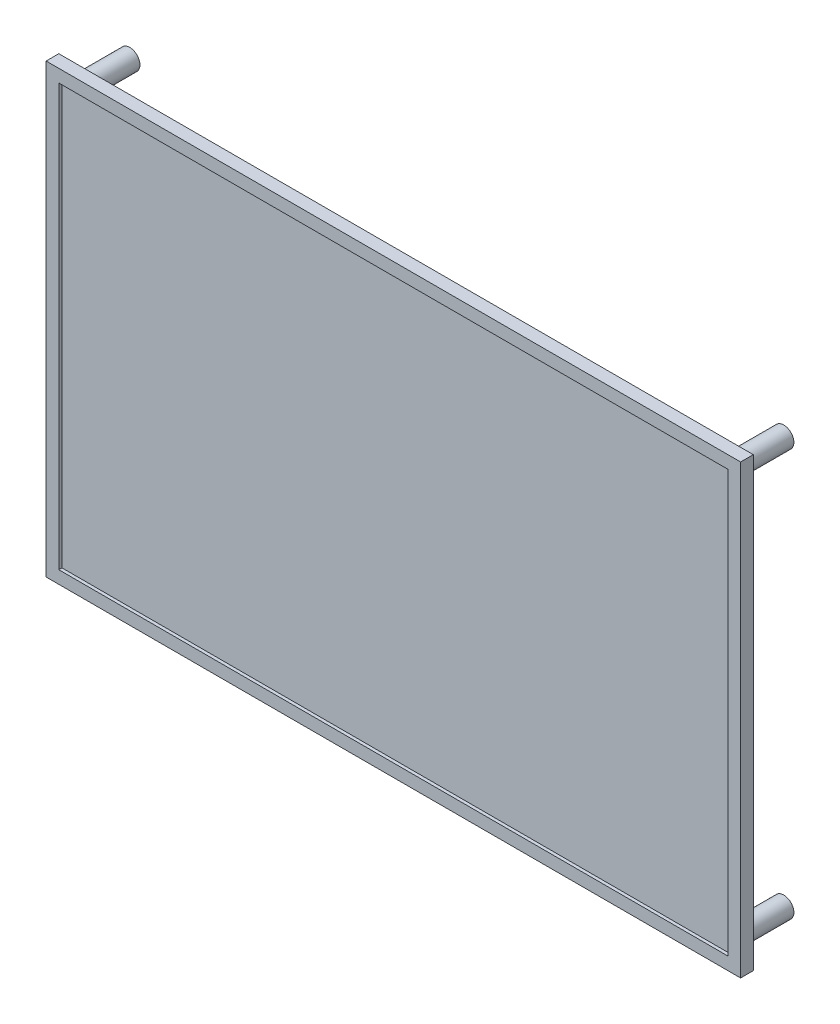
SolidWorks part; units mm, degrees
ref_plane "前视基准面" through (0, 0, 0) normal (0, 0, 1) x (1, 0, 0)
ref_plane "上视基准面" through (0, 0, 0) normal (0, 1, 0) x (1, 0, 0)
ref_plane "右视基准面" through (0, 0, 0) normal (1, 0, 0) x (0, 0, -1)
sketch "草图1" plane through (0, 0, 0) normal (0, 0, 1) x (1, 0, 0)
  line L0 (224.0259, 45.5458) -> (314.7618, 45.5458) construction
  line L1 (224.0259, 72.3541) -> (224.0259, 18.7375) construction
  line L2 (314.7618, 18.7375) -> (314.7618, 72.3541) construction
  line L3 (269.3939, 18.7375) -> (269.3939, 45.5458) construction
  line L4 (224.0259, 18.7375) -> (314.7618, 18.7375) construction
  line L6 (217.8171, 77.6507) -> (320.9707, 77.6507) construction
  line L7 (217.8171, 77.6507) -> (217.8171, 13.4409) construction
  line L8 (217.8171, 13.4409) -> (320.9707, 13.4409) construction
  line L9 (320.9707, 77.6507) -> (320.9707, 13.4409) construction
  line L10 (217.8171, 77.6507) -> (320.9707, 13.4409) construction
  line L11 (217.8171, 13.4409) -> (320.9707, 77.6507) construction
  circle A0 centre (320.9707, 77.6507) radius 1.6
  circle A1 centre (320.9707, 13.4409) radius 1.6
  circle A2 centre (217.8171, 13.4409) radius 1.6
  circle A3 centre (217.8171, 77.6507) radius 1.6
  dimension "D1" = 3.2
extrude "凸台-拉伸1" add sketch "草图1" along normal blind 8
sketch "草图2" plane through (0, 0, 8) normal (0, 0, 1) x (1, 0, 0)
  line L1 (324.1673, 80.7917) -> (214.6204, 80.7917)
  line L2 (324.1673, 80.7917) -> (324.1673, 10.2999)
  line L3 (324.1673, 10.2999) -> (214.6204, 10.2999)
  line L4 (214.6204, 80.7917) -> (214.6204, 10.2999)
  line L5 (324.1673, 80.7917) -> (214.6204, 10.2999) construction
  line L6 (324.1673, 10.2999) -> (214.6204, 80.7917) construction
  point P0 (269.3939, 45.5458)
extrude "凸台-拉伸2" add sketch "草图2" along normal blind 2
sketch "草图3" plane through (0, 0, 10) normal (0, 0, 1) x (1, 0, 0)
  line L0 (216.6204, 78.7917) -> (216.6204, 12.2999)
  line L1 (216.6204, 12.2999) -> (322.1673, 12.2999)
  line L2 (322.1673, 12.2999) -> (322.1673, 78.7917)
  line L3 (322.1673, 78.7917) -> (216.6204, 78.7917)
  line L4 (214.6204, 80.7917) -> (214.6204, 10.2999)
  line L5 (214.6204, 10.2999) -> (324.1673, 10.2999)
  line L6 (324.1673, 10.2999) -> (324.1673, 80.7917)
  line L7 (324.1673, 80.7917) -> (214.6204, 80.7917)
  line L8 (214.6204, 80.7917) -> (214.6204, 10.2999) construction
  line L9 (214.6204, 10.2999) -> (324.1673, 10.2999) construction
  line L10 (324.1673, 10.2999) -> (324.1673, 80.7917) construction
  line L11 (324.1673, 80.7917) -> (214.6204, 80.7917) construction
  dimension "D1" = 0
  dimension "D2" = 2
extrude "切除-拉伸1" cut sketch "草图3" against normal blind 0.5
sketch "草图4" plane through (0, 0, 9.5) normal (0, 0, 1) x (1, 0, 0)
  line L0 (-787.7627, 388.1732) -> (118.9039, 388.1732) construction
sketch "草图5" plane through (0, 0, 9.5) normal (0, 0, 1) x (1, 0, 0)
  line L0 (21.4924, 128.2601) -> (262.8258, 128.2601) construction
